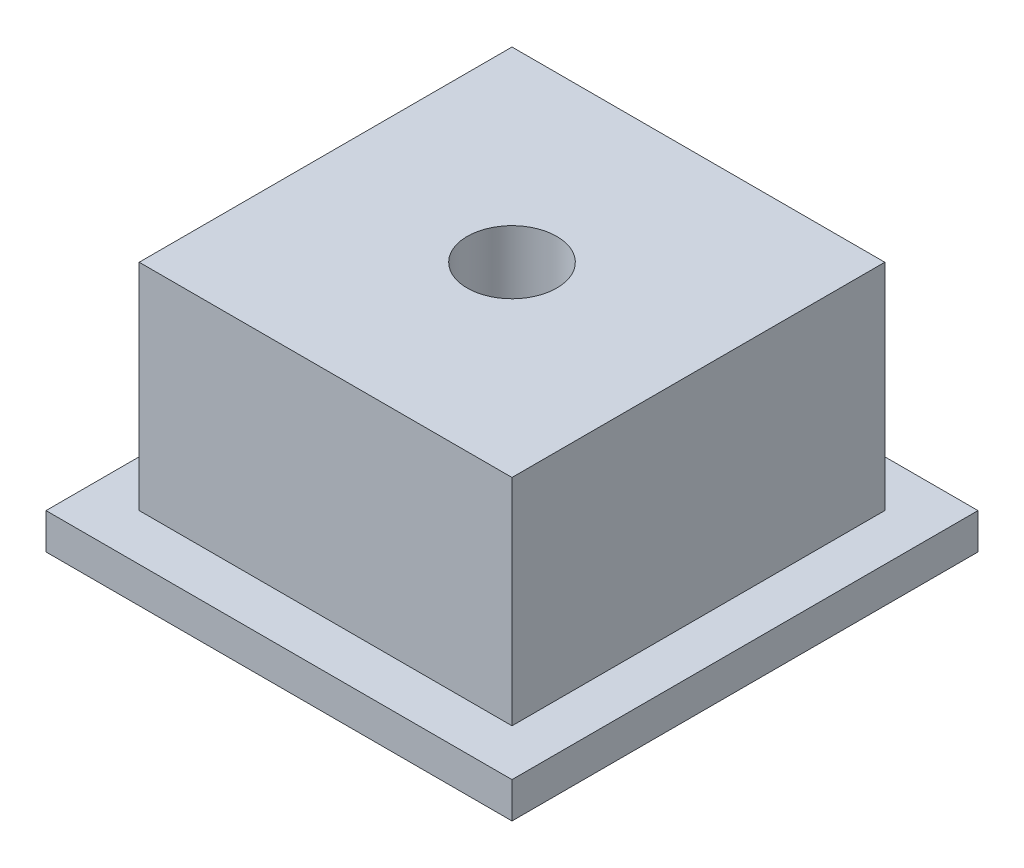
SolidWorks part; units mm, degrees
ref_plane "Front Plane" through (0, 0, 0) normal (0, 0, 1) x (1, 0, 0)
ref_plane "Top Plane" through (0, 0, 0) normal (0, 1, 0) x (1, 0, 0)
ref_plane "Right Plane" through (0, 0, 0) normal (1, 0, 0) x (0, 0, -1)
sketch "Sketch1" plane through (0, 0, 0) normal (0, 1, 0) x (1, 0, 0)
  line L1 (-6.5, -6.5) -> (6.5, -6.5)
  line L2 (-6.5, -6.5) -> (-6.5, 6.5)
  line L3 (-6.5, 6.5) -> (6.5, 6.5)
  line L4 (6.5, -6.5) -> (6.5, 6.5)
  line L5 (-6.5, -6.5) -> (6.5, 6.5) construction
  line L6 (-6.5, 6.5) -> (6.5, -6.5) construction
  point P0 (0, 0)
  dimension "D1" = 13
  dimension "D2" = 13
extrude "Boss-Extrude1" add sketch "Sketch1" along normal blind 1
sketch "Sketch2" plane through (0, 1, 0) normal (0, 1, 0) x (1, 0, 0)
  line L1 (-5.2, -5.2) -> (5.2, -5.2)
  line L2 (-5.2, -5.2) -> (-5.2, 5.2)
  line L3 (-5.2, 5.2) -> (5.2, 5.2)
  line L4 (5.2, -5.2) -> (5.2, 5.2)
  line L5 (-5.2, -5.2) -> (5.2, 5.2) construction
  line L6 (-5.2, 5.2) -> (5.2, -5.2) construction
  point P0 (0, 0)
  dimension "D1" = 10.4
  dimension "D2" = 10.4
extrude "Boss-Extrude2" add sketch "Sketch2" along normal blind 6
sketch "Sketch3" plane through (0, 0, 0) normal (0, -1, 0) x (1, 0, 0)
  circle A0 centre (0, 0) radius 4.5
  dimension "D1" = 9
extrude "Cut-Extrude1" cut sketch "Sketch3" against normal blind 4
sketch "Sketch4" plane through (0, 4, 0) normal (0, -1, 0) x (1, 0, 0)
  circle A0 centre (0, 0) radius 1.25
  dimension "D1" = 2.5
extrude "Cut-Extrude2" cut sketch "Sketch4" against normal through all
